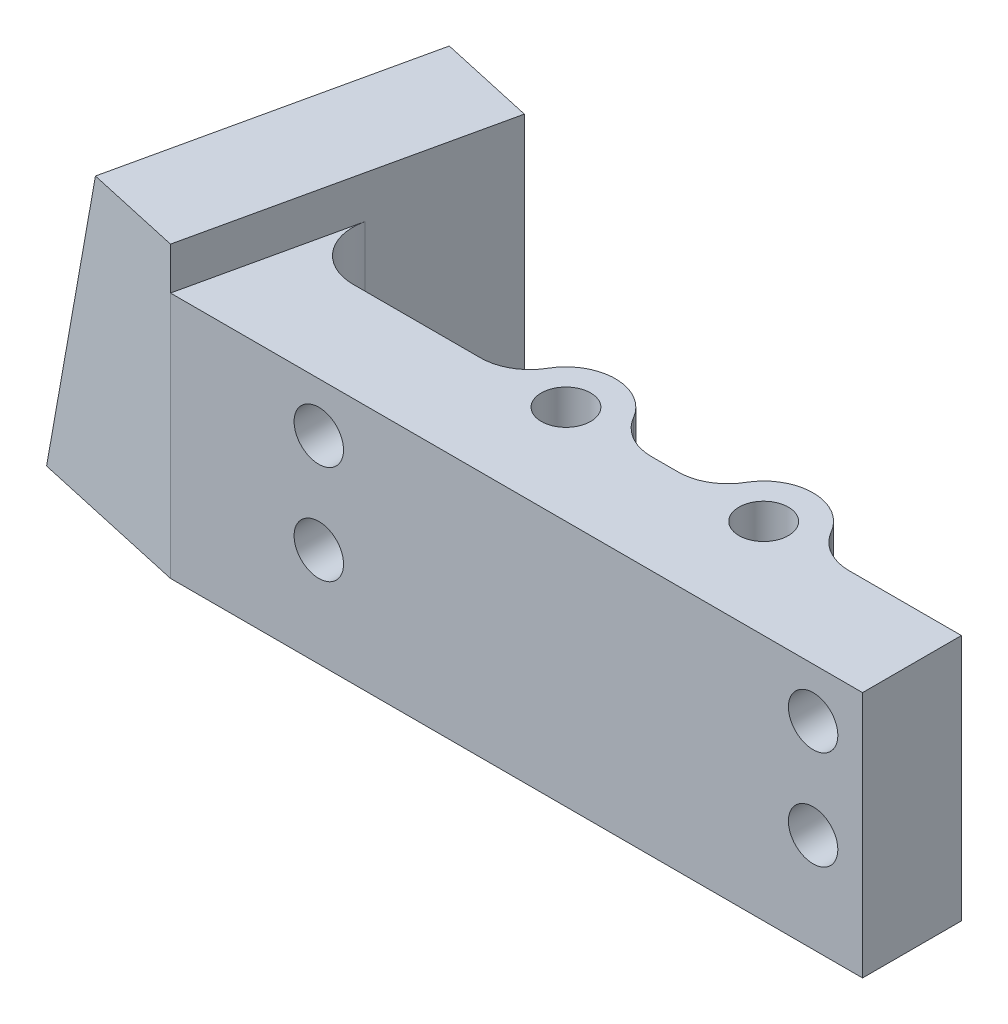
SolidWorks part; units mm, degrees
material "6061 Alloy"
ref_plane "Front Plane" through (0, 0, 0) normal (0, 0, 1) x (1, 0, 0)
ref_plane "Top Plane" through (0, 0, 0) normal (0, 1, 0) x (1, 0, 0)
ref_plane "Right Plane" through (0, 0, 0) normal (1, 0, 0) x (0, 0, -1)
sketch3d "3DSketch1"
  line L0 (0, 0, 0) -> (-228.6, 76.2, 0) construction
  line L1 (-228.6, 76.2, 0) -> (-228.6, 76.2, -50.8) construction
  line L2 (0, 0, 0) -> (-228.6, 76.2, -50.8)
  line L3 (-228.6, 76.2, 0) -> (-228.6, 0, 0) construction
  line L4 (0, 0, 0) -> (-228.6, 0, 0) construction
  dimension "D1" = 228.6
  dimension "D2" = 50.8
  dimension "D3" = 76.2
ref_plane "Plane1" through (0, 0, 0) normal (-0.9283, 0.3094, -0.2063) x (-0.1957, 0.0652, 0.9785)
sketch "Sketch1" plane through (0, 0, 0) normal (0, 1, 0) x (1, 0, 0)
  line L0 (-44.45, -9.6369) -> (44.45, -9.6369)
  line L1 (0, 0) -> (0, -9.6369) construction
  line L2 (-44.45, -9.6369) -> (-56.8476, -6.8819)
  line L3 (-36.1849, 27.5558) -> (-44.45, -9.6369)
  line L4 (-56.8476, -6.8819) -> (-48.5825, 30.3108)
  line L5 (-48.5825, 30.3108) -> (-36.1849, 27.5558)
  line L6 (44.45, -9.6369) -> (44.45, 3.0631)
  line L7 (0, 0) -> (-228.6, 50.8) construction
  line L9 (44.45, 3.0631) -> (-36.1849, 27.5558)
  point P10 (-52.7151, 11.7145)
  dimension "D1" = 88.9
  dimension "D2" = 12.7
  dimension "D3" = 38.1
  dimension "D4" = 12.7
extrude "Boss-Extrude1" add sketch "Sketch1" along normal blind 37.1932 contours L5 L4 L2 L3
sketch "Sketch8" plane through (0, 0, 0) normal (0, 1, 0) x (1, 0, 0)
  line L0 (-36.1849, 27.5558) -> (44.45, 3.0631)
  line L1 (44.45, 3.0631) -> (44.45, -9.6369)
  line L2 (44.45, -9.6369) -> (-44.45, -9.6369)
  line L3 (-44.45, -9.6369) -> (-36.1849, 27.5558)
extrude "Boss-Extrude2" add sketch "Sketch8" along normal blind 31.75
draft "Draft1" type of draft neutral plane draft angle 12.53 faces to draft 1 face at (-52.7151, 18.5966, -11.7145) neutral plane through (0, 37.1932, 0) neutral plane normal (0, 1, 0) parameters "D1"=12.53
sketch "Sketch9" plane through (0, 31.75, 0) normal (0, 1, 0) x (1, 0, 0)
  line L0 (44.45, 3.0631) -> (-41.6278, 3.0631) construction
  line L2 (-36.1849, 27.5558) -> (-44.45, -9.6369) construction
  line L3 (-40.3175, 8.9594) -> (44.45, -9.8778) construction
  line L4 (44.45, -9.6369) -> (44.45, 3.0631) construction
  line L5 (0, 0) -> (-228.6, 50.8) construction
  point P13 (-6.35, 3.0631)
  point P15 (19.05, 3.0631)
  dimension "D1" = 25.4
  dimension "D2" = 25.4
hole_wizard "1/4 (0.25) Diameter Hole2" positions "Sketch11" profile "Sketch12" hole size "1/4" standard "ANSI Inch" end condition up to next
sketch "Sketch11" plane through (0, 31.75, 0) normal (0, 1, 0) x (1, 0, 0)
  point P6 (-6.35, 3.0631)
  point P9 (19.05, 3.0631)
sketch "Sketch12" plane through (-6.35, 31.75, -3.0631) normal (1, 0, 0) x (0, 0, 1)
  line L0 (0, 0) -> (0, 31.75)
  line L1 (0, 31.75) -> (3.175, 31.75)
  line L2 (3.175, 31.75) -> (3.175, 0)
  line L5 (3.175, 0) -> (0, 0)
  line L11 (0, -6.35) -> (0, 107.95) construction
  dimension "Thru Hole Dia." = 6.35
  dimension "Thru Hole Depth" = 31.75
sketch "Sketch13" plane through (0, 31.75, 0) normal (0, 1, 0) x (1, 0, 0)
  line L0 (-36.1849, 27.5558) -> (-39.9106, 10.7906)
  line L1 (-33.7118, 3.0631) -> (-17.3485, 3.0631)
  line L2 (-36.1849, 27.5558) -> (44.45, 3.0631)
  line L3 (4.6485, 3.0631) -> (8.0515, 3.0631)
  line L5 (30.0485, 3.0631) -> (44.45, 3.0631)
  circle A4 centre (-6.35, 3.0631) radius 6.35
  arc A5 (-0.8507, 6.2381) -> (-11.8493, 6.2381) centre (-6.35, 3.0631) ccw
  arc A6 (30.0485, 3.0631) -> (24.5493, 6.2381) centre (30.0485, 9.4131) cw
  circle A7 centre (19.05, 3.0631) radius 6.35
  arc A8 (24.5493, 6.2381) -> (13.5507, 6.2381) centre (19.05, 3.0631) ccw
  arc A9 (8.0515, 3.0631) -> (13.5507, 6.2381) centre (8.0515, 9.4131) ccw
  arc A10 (4.6485, 3.0631) -> (-0.8507, 6.2381) centre (4.6485, 9.4131) cw
  arc A11 (-39.9106, 10.7906) -> (-33.7118, 3.0631) centre (-33.7118, 9.4131) ccw
  arc A12 (-17.3485, 3.0631) -> (-11.8493, 6.2381) centre (-17.3485, 9.4131) ccw
  point P16 (25.4, 3.0631)
  point P19 (12.7, 3.0631)
  point P22 (0, 3.0631)
  point P25 (-41.6278, 3.0631)
  point P29 (-12.7, 3.0631)
  dimension "D3" = 6.35
  dimension "D1" = 3.175
  dimension "D2" = 3.175
extrude "Cut-Extrude2" cut sketch "Sketch13" against normal blind 25.4
hole_wizard "1/4 (0.25) Diameter Hole3" positions "Sketch17" profile "Sketch16" hole size "1/4" standard "ANSI Inch"
sketch "Sketch17" plane through (0, 0, 9.6369) normal (0, 0, 1) x (1, 0, 0)
  line L0 (-44.45, 31.75) -> (44.45, 31.75) construction
  line L1 (-44.45, 0) -> (44.45, 0) construction
  line L2 (44.45, 31.75) -> (44.45, 0) construction
  point P0 (38.1, 25.4)
  point P2 (38.1, 12.7)
  point P4 (-25.4, 25.4)
  point P6 (-25.4, 12.7)
  dimension "D1" = 6.35
  dimension "D2" = 12.7
  dimension "D3" = 6.35
  dimension "D4" = 63.5
sketch "Sketch16" plane through (38.1, 25.4, 9.6369) normal (1, 0, 0) x (0, -1, 0)
  line L0 (0, 0) -> (0, 33.6577)
  line L1 (0, 33.6577) -> (3.175, 31.75)
  line L2 (3.175, 31.75) -> (3.175, 0)
  line L5 (3.175, 0) -> (0, 0)
  line L10 (0, 33.6577) -> (-3.175, 31.75) construction
  line L11 (0, -6.35) -> (0, 107.95) construction
  dimension "Hole Dia." = 6.35
  dimension "Hole Depth" = 31.75
  dimension "Drill Angle" = 118
hole_wizard "1/4-20 Tapped Hole1" positions "Sketch20" profile "Sketch19" tap size "1/4-20" standard "ANSI Inch"
sketch "Sketch20" plane through (-57.9232, 13.1871, -12.8718) normal (-0.9529, 0.217, -0.2118) x (-0.2065, 0.047, 0.9773)
  line L0 (20.2121, 23.6459) -> (-17.8437, 25.4806) construction
  line L1 (18.3774, -14.4105) -> (-19.6784, -12.5758) construction
  line L2 (20.2121, 23.6459) -> (18.3774, -14.4105) construction
  line L3 (-17.8437, 25.4806) -> (-19.6784, -12.5758) construction
  line L4 (20.2117, 23.6458) -> (18.3776, -14.4101) construction
  point P0 (13.5637, 17.6091)
  point P2 (12.3406, -7.7621)
  point P4 (-8.9413, 12.3367)
  point P6 (-9.5529, -0.3492)
  point P18 (12.3406, -7.7621)
  dimension "D1" = 12.7
  dimension "D2" = 12.7
  dimension "D3" = 6.35
  dimension "D4" = 6.35
  dimension "D5" = 6.35
  dimension "D6" = 9.525
  dimension "D7" = 6.35
  dimension "D8" = 9.525
sketch "Sketch19" plane through (-56.8149, 30.9945, 0.3843) normal (0.0038, 0.7071, 0.7071) x (-0.3031, -0.673, 0.6747)
  line L0 (0, 0) -> (0, 14.2338)
  line L1 (0, 14.2338) -> (2.5527, 12.7)
  line L2 (2.5527, 12.7) -> (2.5527, 0)
  line L5 (2.5527, 0) -> (0, 0)
  line L10 (0, 14.2338) -> (-2.5527, 12.7) construction
  line L11 (0, -6.35) -> (0, 107.95) construction
  dimension "Tap Drill Dia." = 5.1054
  dimension "Tap Drill Depth" = 12.7
  dimension "Drill Angle" = 118
sketch "Sketch22" plane through (0, 6.35, 0) normal (0, 1, 0) x (1, 0, 0)
  line L0 (-36.1849, 27.5558) -> (-39.9106, 10.7906) construction
  line L1 (-33.7118, 3.0631) -> (-17.3485, 3.0631) construction
  line L2 (4.6485, 3.0631) -> (8.0515, 3.0631) construction
  line L4 (-38.3403, 17.8569) -> (-39.9106, 10.7906)
  line L5 (-33.7118, 3.0631) -> (-29.9666, 3.0631)
  line L6 (4.6485, 3.0631) -> (8.0515, 3.0631)
  line L8 (-31.0803, 22.687) -> (-16.686, 18.3148)
  line L9 (44.45, 3.0631) -> (-36.1849, 27.5558) construction
  line L10 (-36.8757, 24.4474) -> (-25.5301, 3.0631) construction
  line L11 (-32.944, 20.424) -> (-26.2244, 7.7588)
  line L12 (-35.3882, 18.2565) -> (-28.5642, 5.3946)
  line L13 (-32.6053, 13.0112) -> (-29.8006, 14.4993) construction
  line L14 (-25.5301, 3.0631) -> (-12.5721, 17.0652) construction
  line L15 (-15.9823, 15.7176) -> (-23.6569, 7.4245)
  line L16 (-13.8923, 13.3015) -> (-20.9002, 5.7288)
  line L17 (-17.886, 8.9859) -> (-20.2163, 11.1424) construction
  line L18 (-4.8849, 14.7302) -> (13.1034, 9.2663)
  line L19 (-19.7351, 3.0631) -> (-17.3485, 3.0631)
  line L20 (-12.5721, 17.0652) -> (-6.35, 9.4131) construction
  line L21 (-3.9063, 8.924) -> (-6.5779, 12.2097)
  line L22 (-9.4536, 10.7136) -> (-11.4954, 13.2247)
  line L23 (-8.2294, 14.2407) -> (-10.6928, 12.2376) construction
  arc A0 (-39.9106, 10.7906) -> (-33.7118, 3.0631) centre (-33.7118, 9.4131) ccw construction
  arc A1 (-17.3485, 3.0631) -> (-11.8493, 6.2381) centre (-17.3485, 9.4131) ccw construction
  arc A2 (-0.8507, 6.2381) -> (-11.8493, 6.2381) centre (-6.35, 3.0631) ccw construction
  arc A3 (-0.8507, 6.2381) -> (4.6485, 3.0631) centre (4.6485, 9.4131) ccw construction
  arc A4 (8.0515, 3.0631) -> (13.5507, 6.2381) centre (8.0515, 9.4131) ccw construction
  arc A5 (24.5493, 6.2381) -> (13.5507, 6.2381) centre (19.05, 3.0631) ccw construction
  arc A7 (-39.9106, 10.7906) -> (-33.7118, 3.0631) centre (-33.7118, 9.4131) ccw
  arc A8 (-17.3485, 3.0631) -> (-11.8493, 6.2381) centre (-17.3485, 9.4131) ccw
  arc A9 (-0.8507, 6.2381) -> (-3.9063, 8.924) centre (-6.35, 3.0631) ccw
  arc A10 (-0.8507, 6.2381) -> (4.6485, 3.0631) centre (4.6485, 9.4131) ccw
  arc A11 (8.0515, 3.0631) -> (13.5507, 6.2381) centre (8.0515, 9.4131) ccw
  arc A12 (13.9236, 6.8105) -> (13.5507, 6.2381) centre (19.05, 3.0631) ccw
  arc A13 (13.9236, 6.8105) -> (13.1034, 9.2663) centre (12.6421, 7.7473) ccw
  arc A14 (-9.8182, 8.3823) -> (-11.8493, 6.2381) centre (-6.35, 3.0631) ccw
  arc A15 (-6.5779, 12.2097) -> (-4.8849, 14.7302) centre (-5.3462, 13.2112) cw
  arc A16 (-9.4536, 10.7136) -> (-9.8182, 8.3823) centre (-10.6853, 9.7121) cw
  arc A17 (-13.8923, 13.3015) -> (-11.4954, 13.2247) centre (-12.7271, 12.2232) cw
  arc A18 (-20.9002, 5.7288) -> (-19.7351, 3.0631) centre (-19.7351, 4.6506) ccw
  arc A19 (-23.6569, 7.4245) -> (-26.2244, 7.7588) centre (-24.822, 8.5028) cw
  arc A20 (-16.686, 18.3148) -> (-15.9823, 15.7176) centre (-17.1474, 16.7958) cw
  arc A21 (-32.944, 20.424) -> (-31.0803, 22.687) centre (-31.5417, 21.1681) cw
  arc A22 (-28.5642, 5.3946) -> (-29.9666, 3.0631) centre (-29.9666, 4.6506) cw
  arc A23 (-35.3882, 18.2565) -> (-38.3403, 17.8569) centre (-36.7906, 17.5125) ccw
  point P31 (-31.2029, 13.7552)
  point P37 (-19.0511, 10.0641)
  point P45 (-9.4611, 13.2391)
  point P49 (-8.1776, 9.1444)
  point P54 (-23.3672, 3.0631)
  dimension "D6" = 1.5875
  dimension "D7" = 1.5875
  dimension "D1" = 3.175
  dimension "D2" = 3.175
  dimension "D3" = 25.4
  dimension "D4" = 3.175
  dimension "D5" = 3.175
